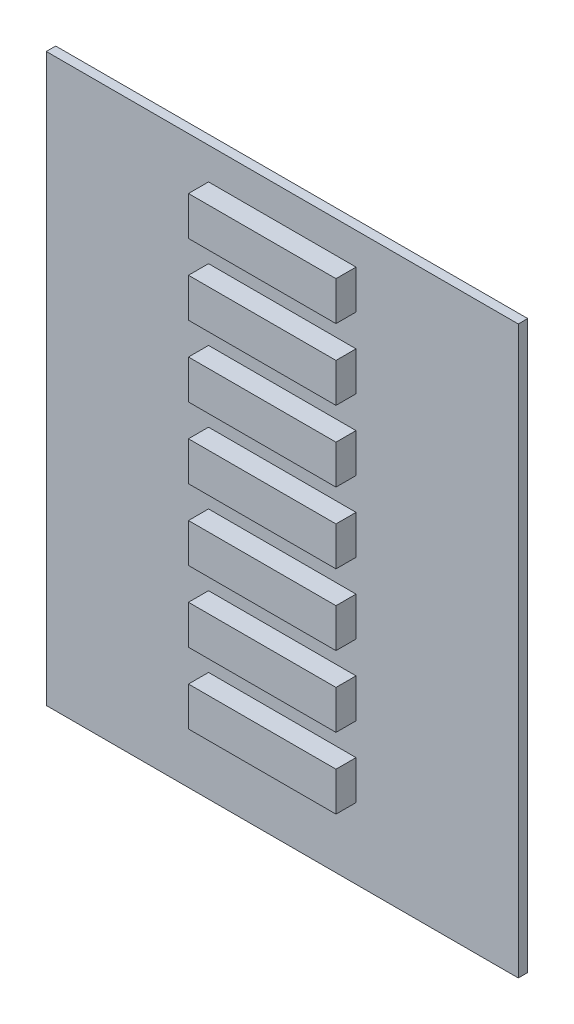
SolidWorks part; units mm, degrees
ref_plane "Front" through (0, 0, 0) normal (0, 0, 1) x (1, 0, 0)
ref_plane "Top" through (0, 0, 0) normal (0, 1, 0) x (1, 0, 0)
ref_plane "Right" through (0, 0, 0) normal (1, 0, 0) x (0, 0, -1)
ref_plane "MOUNTING SURFACE" through (0, 0, -42.6) normal (0, 0, 1) x (1, 0, 0)
sketch "Sketch1" plane through (0, 0, -42.6) normal (0, 0, 1) x (1, 0, 0)
  line L1 (-40, 48) -> (40, 48)
  line L2 (-40, 48) -> (-40, -48)
  line L3 (-40, -48) -> (40, -48)
  line L4 (40, 48) -> (40, -48)
  line L5 (-40, 48) -> (40, -48) construction
  line L6 (-40, -48) -> (40, 48) construction
  point P0 (0, 0)
  dimension "D1" = 80
  dimension "D2" = 96
extrude "Boss-Extrude1" add sketch "Sketch1" along normal blind 1.6
sketch "Sketch3" plane through (0, 0, -42.6) normal (0, 0, 1) x (1, 0, 0)
  line L0 (12.5, 50) -> (12.5, -50) construction
  line L1 (12.5, -50) -> (-12.5, -50) construction
  line L2 (-12.5, -50) -> (-12.5, 50) construction
  line L3 (-12.5, 50) -> (12.5, 50) construction
  line L4 (88.99, 0) -> (-88.99, 0) construction
  line L5 (0, -55) -> (0, 55) construction
  line L6 (55, 36) -> (-55, 36) construction
  line L7 (-12.5, 42.6) -> (12.5, 42.6)
  line L8 (-12.5, 42.6) -> (-12.5, 36)
  line L9 (-12.5, 36) -> (12.5, 36)
  line L10 (12.5, 42.6) -> (12.5, 36)
  line L11 (-12.5, 30.6) -> (12.5, 30.6)
  line L12 (-12.5, 30.6) -> (-12.5, 24)
  line L13 (-12.5, 24) -> (12.5, 24)
  line L14 (12.5, 30.6) -> (12.5, 24)
  line L15 (-12.5, 18.6) -> (12.5, 18.6)
  line L16 (-12.5, 18.6) -> (-12.5, 12)
  line L17 (-12.5, 12) -> (12.5, 12)
  line L18 (12.5, 18.6) -> (12.5, 12)
  line L19 (-12.5, 6.6) -> (12.5, 6.6)
  line L20 (-12.5, 6.6) -> (-12.5, 0)
  line L21 (-12.5, 0) -> (12.5, 0)
  line L22 (12.5, 6.6) -> (12.5, 0)
  line L23 (-12.5, -5.4) -> (12.5, -5.4)
  line L24 (-12.5, -5.4) -> (-12.5, -12)
  line L25 (-12.5, -12) -> (12.5, -12)
  line L26 (12.5, -5.4) -> (12.5, -12)
  line L27 (-12.5, -17.4) -> (12.5, -17.4)
  line L28 (-12.5, -17.4) -> (-12.5, -24)
  line L29 (-12.5, -24) -> (12.5, -24)
  line L30 (12.5, -17.4) -> (12.5, -24)
  line L31 (-12.5, -29.4) -> (12.5, -29.4)
  line L32 (-12.5, -29.4) -> (-12.5, -36)
  line L33 (-12.5, -36) -> (12.5, -36)
  line L34 (12.5, -29.4) -> (12.5, -36)
  line L35 (55, 24) -> (-55, 24) construction
  line L36 (55, 12) -> (-55, 12) construction
  line L37 (55, 0) -> (-55, 0) construction
  line L38 (55, -12) -> (-55, -12) construction
  line L39 (55, -24) -> (-55, -24) construction
  line L40 (55, -36) -> (-55, -36) construction
  point P8 (0, 50)
  point P9 (0, -50)
  dimension "D1" = 50
  dimension "D2" = 50
  dimension "D3" = 25
  dimension "D4" = 6.6
extrude "Boss-Extrude2" add sketch "Sketch3" along normal blind 5
